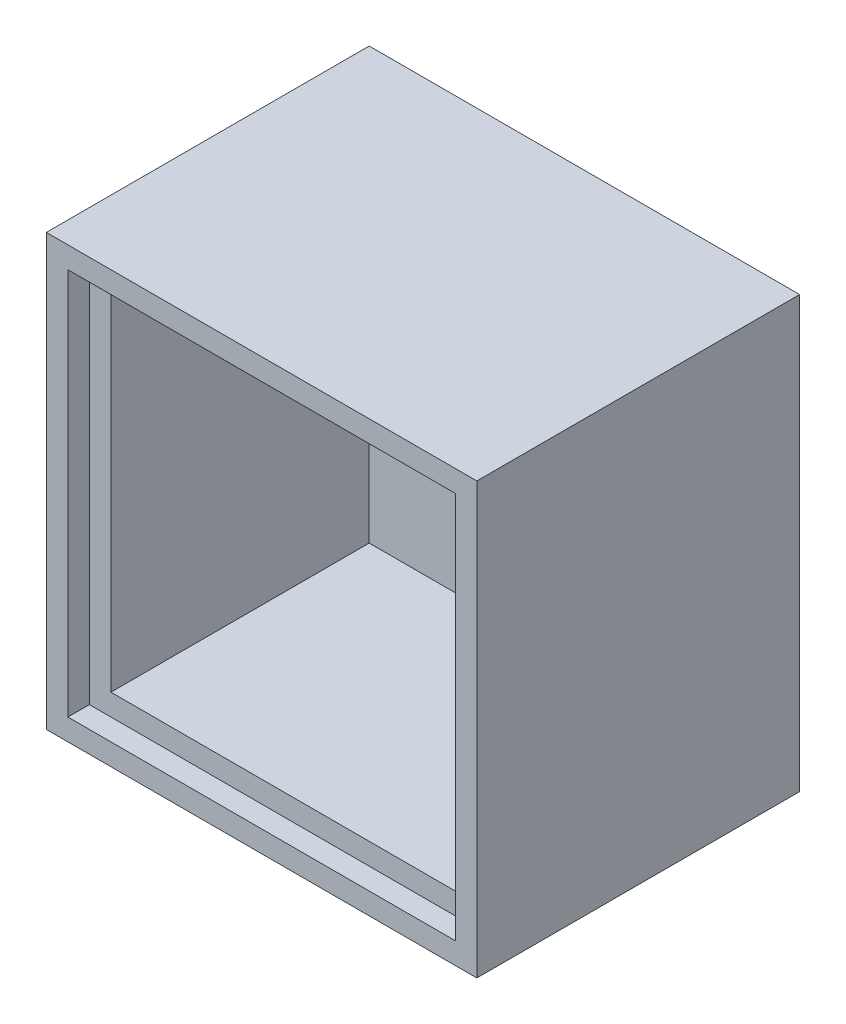
SolidWorks part; units mm, degrees
material "Balsa"
ref_plane "Front Plane" through (0, 0, 0) normal (0, 0, 1) x (1, 0, 0)
ref_plane "Top Plane" through (0, 0, 0) normal (0, 1, 0) x (1, 0, 0)
ref_plane "Right Plane" through (0, 0, 0) normal (1, 0, 0) x (0, 0, -1)
sketch "Sketch2" plane through (0, 0, 0) normal (0, 0, 1) x (1, 0, 0)
  line L1 (-50, 50) -> (50, 50)
  line L2 (-50, 50) -> (-50, -50)
  line L3 (-50, -50) -> (50, -50)
  line L4 (50, 50) -> (50, -50)
  line L5 (-50, 50) -> (50, -50) construction
  line L6 (-50, -50) -> (50, 50) construction
  point P0 (0, 0)
  dimension "D1" = 100
extrude "Boss-Extrude1" add sketch "Sketch2" along normal blind 75
shell "Shell1" thickness 10
sketch "Sketch3" plane through (0, 0, 75) normal (0, 0, 1) x (1, 0, 0)
  line L1 (-45, -45) -> (45, -45)
  line L2 (-45, -45) -> (-45, 45)
  line L3 (-45, 45) -> (45, 45)
  line L4 (45, -45) -> (45, 45)
  line L5 (-45, -45) -> (45, 45) construction
  line L6 (-45, 45) -> (45, -45) construction
  point P0 (0, 0)
  dimension "D1" = 90
extrude "Cut-Extrude1" cut sketch "Sketch3" against normal blind 5
sketch "Sketch4" plane through (0, 0, 10) normal (0, 0, 1) x (1, 0, 0)
  line L0 (9.8514, 20) -> (20, 20)
  line L1 (20, 20) -> (20, 11.8811)
  line L2 (40, -40) -> (40, 40) construction
  line L3 (40, 40) -> (-40, 40) construction
  dimension "D1" = 20
  dimension "D2" = 20
